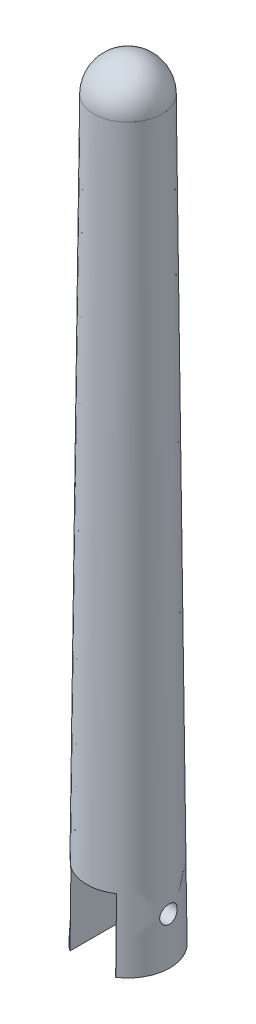
SolidWorks part; units mm, degrees
ref_plane "Front Plane" through (0, 0, 0) normal (0, 0, 1) x (1, 0, 0)
ref_plane "Top Plane" through (0, 0, 0) normal (0, 1, 0) x (1, 0, 0)
ref_plane "Right Plane" through (0, 0, 0) normal (1, 0, 0) x (0, 0, -1)
sketch "Sketch1" plane through (0, 0, 0) normal (0, 1, 0) x (1, 0, 0)
  circle A0 centre (0, 0) radius 4.775
  dimension "D1" = 9.55
ref_plane "Plane1" through (0, 83.85, 0) normal (0, 1, 0) x (1, 0, 0)
sketch "Sketch2" plane through (0, 83.85, 0) normal (0, 1, 0) x (1, 0, 0)
  circle A0 centre (0, 0) radius 3.9
  dimension "D1" = 7.8
loft "Loft1" add profiles "Sketch1", "Sketch2"
sketch "Sketch3" plane through (0, 83.85, 0) normal (0, 1, 0) x (1, 0, 0)
  line L0 (0, 3.9) -> (0, -3.9)
  circle A1 centre (0, 0) radius 3.9
  arc A2 (0, 3.9) -> (0, -3.9) centre (0, 0) ccw
  dimension "D1" = 0
revolve "Revolve1" add sketch "Sketch3" angle 180 about L0
sketch "Sketch4" plane through (0, 0, 0) normal (1, 0, 0) x (0, 0, -1)
  line L0 (0, 5.2526) -> (0, -5.2526) construction
  line L1 (-7.8926, 0) -> (2.3, 0)
  line L2 (-7.8926, 0) -> (-7.8926, 8.2)
  line L3 (-7.8926, 8.2) -> (2.3, 8.2)
  line L4 (2.3, 0) -> (2.3, 8.2)
  dimension "D1" = 8.2
  dimension "D2" = 2.3
extrude "Cut-Extrude1" cut sketch "Sketch4" against normal mid plane 5.2
sketch "Sketch5" plane through (2.6, 0, 0) normal (-1, 0, 0) x (0, 0, 1)
  line L0 (0, -5.2526) -> (0, 5.2526) construction
  line L1 (5.2055, 0) -> (-5.2055, 0) construction
  circle A0 centre (0, 5.3) radius 1
  dimension "D1" = 2
  dimension "D2" = 5.3
extrude "Cut-Extrude2" cut sketch "Sketch5" against normal through all both and the other way through all
